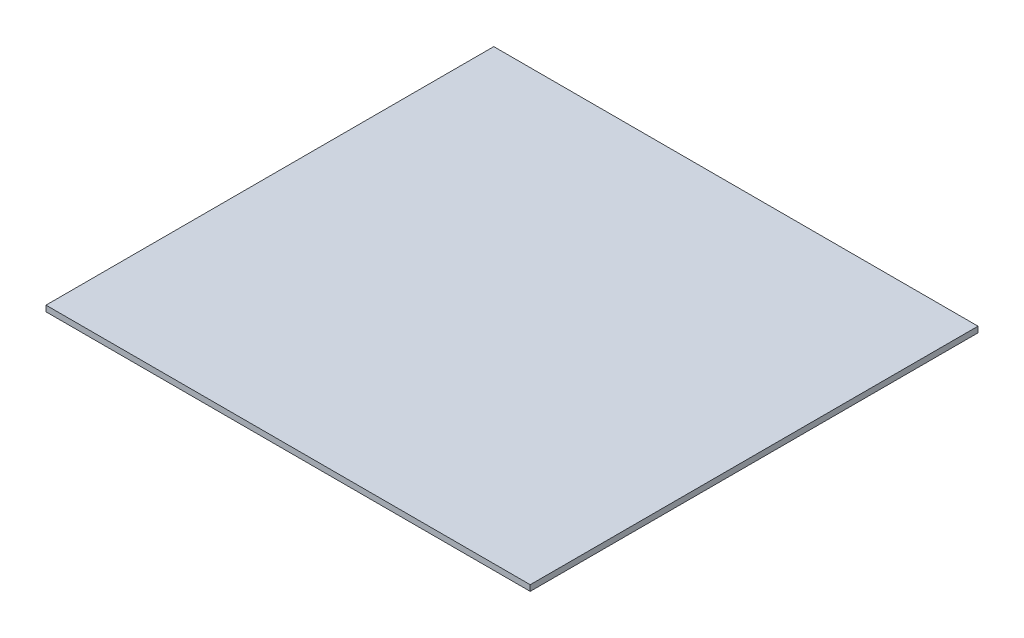
SolidWorks part; units mm, degrees
ref_plane "Front Plane" through (0, 0, 0) normal (0, 0, 1) x (1, 0, 0)
ref_plane "Top Plane" through (0, 0, 0) normal (0, 1, 0) x (1, 0, 0)
ref_plane "Right Plane" through (0, 0, 0) normal (1, 0, 0) x (0, 0, -1)
sketch "Sketch1" plane through (0, 0, 0) normal (0, 1, 0) x (1, 0, 0)
  line L1 (-62.45, 57.75) -> (62.45, 57.75)
  line L2 (-62.45, 57.75) -> (-62.45, -57.75)
  line L3 (-62.45, -57.75) -> (62.45, -57.75)
  line L4 (62.45, 57.75) -> (62.45, -57.75)
  line L5 (-62.45, 57.75) -> (62.45, -57.75) construction
  line L6 (-62.45, -57.75) -> (62.45, 57.75) construction
  point P0 (0, 0)
  dimension "D1" = 124.9
  dimension "D2" = 115.5
extrude "Boss-Extrude1" add sketch "Sketch1" along normal blind 1.5
